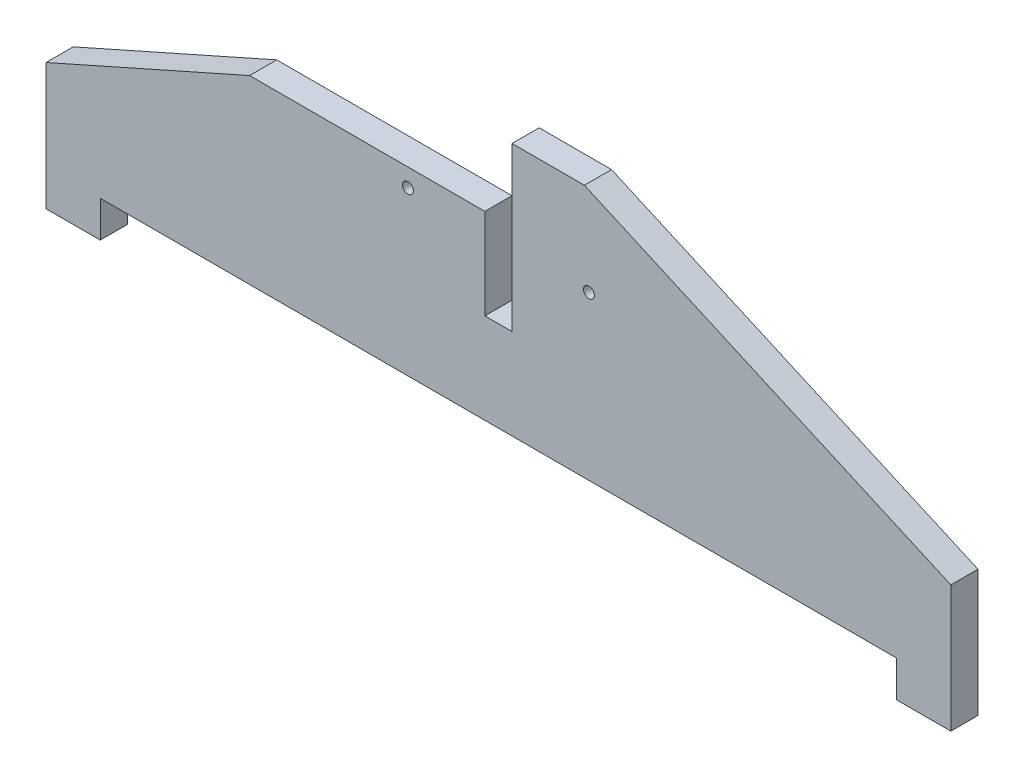
SolidWorks part; units mm, degrees
ref_plane "Plan de face" through (0, 0, 0) normal (0, 0, 1) x (1, 0, 0)
ref_plane "Plan de dessus" through (0, 0, 0) normal (0, 1, 0) x (1, 0, 0)
ref_plane "Plan de droite" through (0, 0, 0) normal (1, 0, 0) x (0, 0, -1)
sketch "Esquisse1" plane through (0, 0, 0) normal (0, 0, 1) x (1, 0, 0)
  line L0 (0, 0) -> (30, 0)
  line L1 (30, 0) -> (30, 20)
  line L2 (30, 20) -> (470, 20)
  line L3 (470, 20) -> (470, 0)
  line L4 (470, 0) -> (500, 0)
  line L5 (500, 0) -> (500, 70)
  line L7 (257.5, 160) -> (257.5, 70)
  line L8 (257.5, 70) -> (242.5, 70)
  line L9 (242.5, 70) -> (242.5, 120)
  line L11 (0, 70) -> (0, 0)
  line L12 (250, 70) -> (250, 52.9687) construction
  line L13 (257.5, 160) -> (297.5, 160)
  line L14 (297.5, 160) -> (500, 70)
  line L15 (242.5, 120) -> (112.5, 120)
  line L16 (112.5, 120) -> (0, 70)
  line L17 (500, 70) -> (250, 181.1111) construction
  line L18 (250, 181.1111) -> (0, 70) construction
  circle A0 centre (200, 110) radius 3
  circle A1 centre (300, 110) radius 3
  point P15 (250, 20)
  dimension "D10" = 6
  dimension "D1" = 15
  dimension "D2" = 500
  dimension "D3" = 30
  dimension "D4" = 50
  dimension "D5" = 70
  dimension "D6" = 90
  dimension "D7" = 20
  dimension "D8" = 50
  dimension "D9" = 40
  dimension "D11" = 10
  dimension "D12" = 100
extrude "Boss.-Extru.1" add sketch "Esquisse1" along normal blind 15
